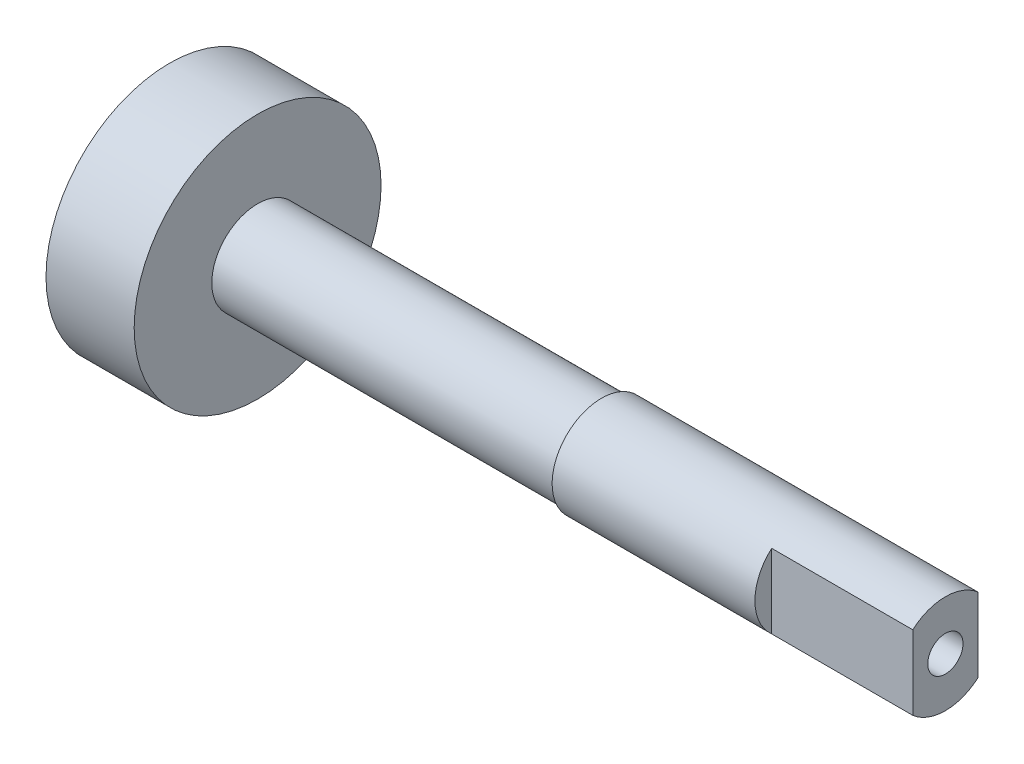
SolidWorks part; units mm, degrees
ref_plane "Front Plane" through (0, 0, 0) normal (0, 0, 1) x (1, 0, 0)
ref_plane "Top Plane" through (0, 0, 0) normal (0, 1, 0) x (1, 0, 0)
ref_plane "Right Plane" through (0, 0, 0) normal (1, 0, 0) x (0, 0, -1)
sketch "Sketch1" plane through (0, 0, 0) normal (1, 0, 0) x (0, 0, -1)
  circle A0 centre (0, 0) radius 2.8
  dimension "D1" = 5.6
extrude "Boss-Extrude1" add sketch "Sketch1" along normal mid plane 39
sketch "Sketch2" plane through (19.5, 0, 0) normal (1, 0, 0) x (0, 0, -1)
  line L0 (-1.85, 2.1018) -> (-1.85, -2.1018)
  line L1 (1.85, 2.1018) -> (1.85, -2.1018)
  arc A0 (-1.85, 2.1018) -> (-1.85, -2.1018) centre (0, 0) ccw
  arc A1 (1.85, -2.1018) -> (1.85, 2.1018) centre (0, 0) ccw
  dimension "D3" = 5.6
  dimension "D1" = 3.7
  dimension "D2" = 1.85
extrude "Cut-Extrude1" cut sketch "Sketch2" against normal blind 8
sketch "Sketch3" plane through (19.5, 0, 0) normal (1, 0, 0) x (0, 0, -1)
  circle A0 centre (0, 0) radius 1
  dimension "D1" = 2
extrude "Cut-Extrude2" cut sketch "Sketch3" against normal blind 6
ref_plane "Plane1" through (-19.5, 0, 0) normal (-1, 0, 0) x (0, 0, 1)
sketch "Sketch5" plane through (-19.5, 0, 0) normal (-1, 0, 0) x (0, 0, 1)
  circle A0 centre (0, 0) radius 7
  dimension "D1" = 14
extrude "Boss-Extrude2" add sketch "Sketch5" along normal blind 5 contours A0
ref_plane "Plane3" through (0, 0, 0) normal (1, 0, 0) x (0, 0, -1)
sketch "Sketch7" plane through (0, 0, 0) normal (1, 0, 0) x (0, 0, -1)
  circle A0 centre (0, 0) radius 2.6
  circle A1 centre (0, 0) radius 2.9
  dimension "D1" = 5.2
  dimension "D2" = 5.8
extrude "Cut-Extrude3" cut sketch "Sketch7" against normal blind 19.5
equation "\"shaftdiameter\"= 5.6"
equation "\"D1@Sketch1\"=\"shaftdiameter\""
equation "\"D3@Sketch2\"=\"shaftdiameter\""
equation "\"motor_cut\"= 8"
equation "\"D1@Cut-Extrude1\"=\"motor_cut\""
equation "\"D1@Sketch7\"=5.2"
equation "\"D2@Sketch7\"=\"shaftdiameter\"+.2"
